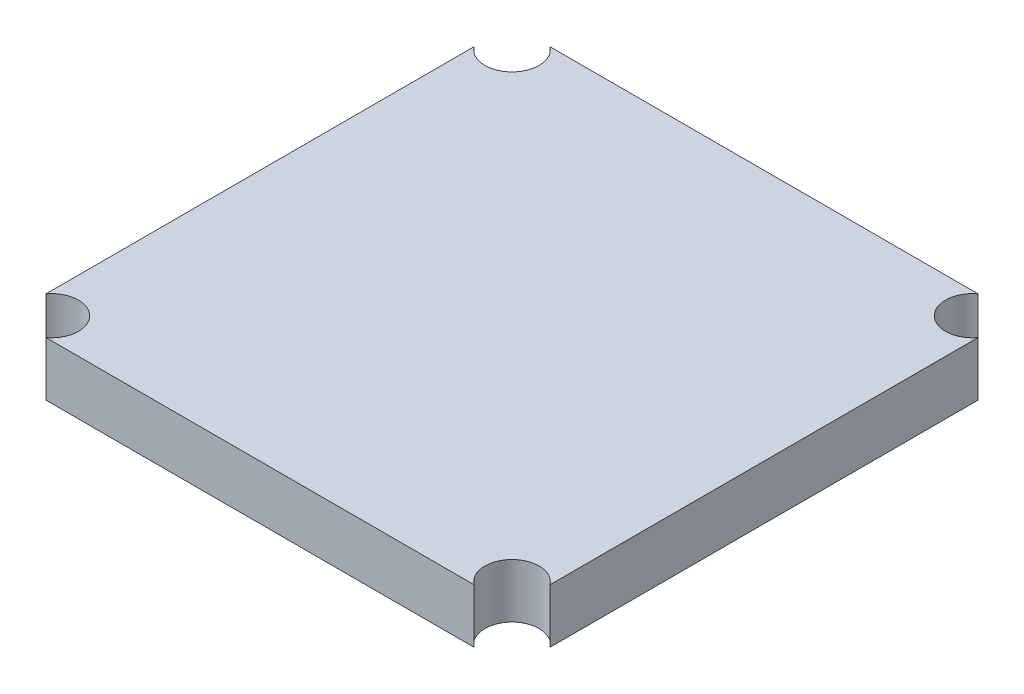
SolidWorks part; units mm, degrees
ref_plane "Front Plane" through (0, 0, 0) normal (0, 0, 1) x (1, 0, 0)
ref_plane "Top Plane" through (0, 0, 0) normal (0, 1, 0) x (1, 0, 0)
ref_plane "Right Plane" through (0, 0, 0) normal (1, 0, 0) x (0, 0, -1)
sketch "Sketch1" plane through (0, 0, 0) normal (0, 1, 0) x (1, 0, 0)
  line L0 (-30, 0) -> (-19, 0) construction
  line L1 (-19, -19) -> (19, -19)
  line L2 (-19, -19) -> (-19, 19)
  line L3 (-19, 19) -> (19, 19)
  line L4 (19, -19) -> (19, 19)
  line L5 (-19, -19) -> (19, 19) construction
  line L6 (-19, 19) -> (19, -19) construction
  line L8 (0, 18.0312) -> (18.0312, 0)
  line L9 (0, 18.0312) -> (-18.0312, 0)
  line L10 (-18.0312, 0) -> (0, -18.0312)
  line L11 (18.0312, 0) -> (0, -18.0312)
  line L12 (0, 18.0312) -> (0, -18.0312) construction
  line L13 (-18.0312, 0) -> (18.0312, 0) construction
  circle A1 centre (-24.5, 0) radius 1.5
  circle A2 centre (0, 0) radius 30
  circle A3 centre (0, 0) radius 19
  circle A4 centre (0, 18.0312) radius 1.75
  point P0 (0, 0)
  point P18 (0, 0)
  point P19 (0, 0)
  dimension "D3" = 3
  dimension "D6" = 60
  dimension "D7" = 38
  dimension "D8" = 3.5
  dimension "D2" = 38
  dimension "D4" = 25.5
  dimension "D5" = 25.5
sketch "Sketch2" plane through (0, 0, 0) normal (0, 1, 0) x (1, 0, 0)
  line L0 (-13.95, 11.85) -> (-13.95, -11.85)
  line L1 (-12.75, -12.75) -> (12.75, -12.75) construction
  line L2 (-12.75, -12.75) -> (-12.75, 12.75) construction
  line L3 (-12.75, 12.75) -> (12.75, 12.75) construction
  line L4 (12.75, -12.75) -> (12.75, 12.75) construction
  line L5 (-12.75, -12.75) -> (12.75, 12.75) construction
  line L6 (-12.75, 12.75) -> (12.75, -12.75) construction
  line L7 (11.85, 13.95) -> (-11.85, 13.95)
  line L8 (13.95, -11.85) -> (13.95, 11.85)
  line L9 (-11.85, -13.95) -> (11.85, -13.95)
  circle A0 centre (-12.75, 12.75) radius 1.5
  circle A1 centre (12.75, 12.75) radius 1.5
  circle A2 centre (12.75, -12.75) radius 1.5
  circle A3 centre (-12.75, -12.75) radius 1.5
  point P0 (0, 0)
  point P16 (0, 0)
  point P24 (0, 0)
  dimension "D2" = 3
  dimension "D1" = 25.5
  dimension "D4" = 1.2
  dimension "D3" = 4
  dimension "D5" = 4
extrude "Flight Computer" add sketch "Sketch2" along normal blind 3 contours A3 L9 A2 L8 A1 L7 A0 L0
